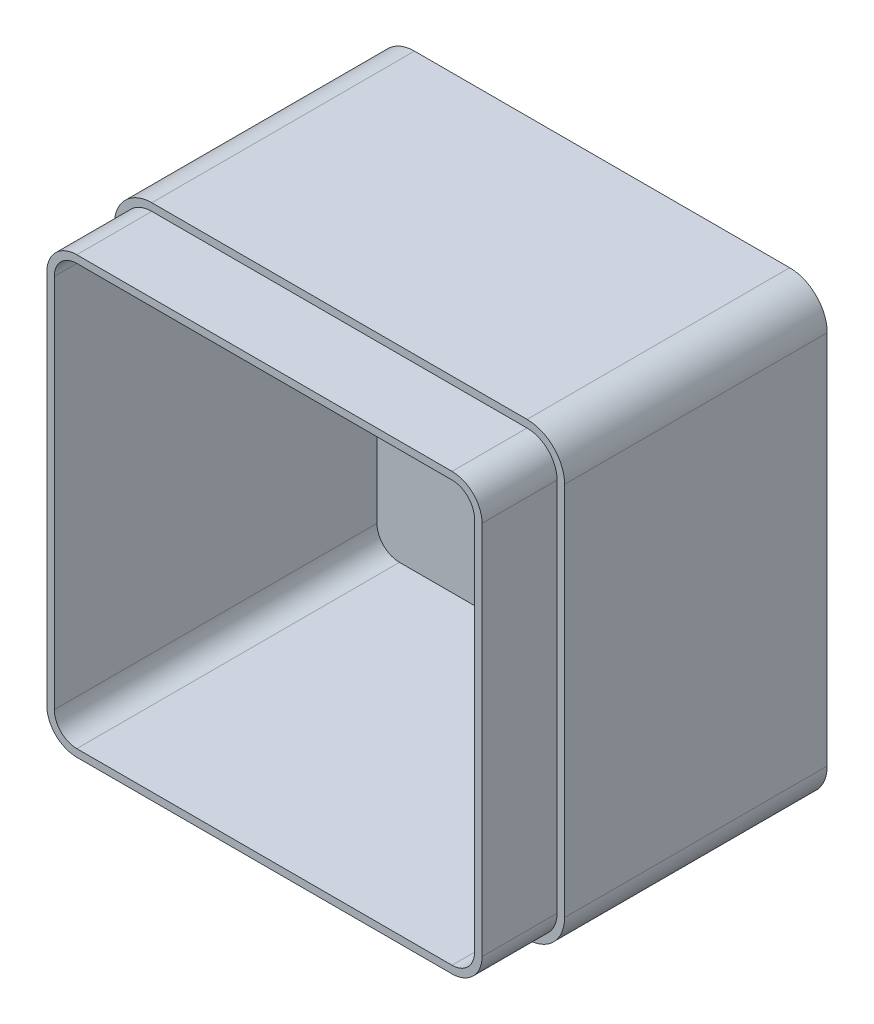
SolidWorks part; units mm, degrees
ref_plane "Front Plane" through (0, 0, 0) normal (0, 0, 1) x (1, 0, 0)
ref_plane "Top Plane" through (0, 0, 0) normal (0, 1, 0) x (1, 0, 0)
ref_plane "Right Plane" through (0, 0, 0) normal (1, 0, 0) x (0, 0, -1)
sketch "Sketch1" plane through (0, 0, 0) normal (0, 0, 1) x (1, 0, 0)
  line L1 (0, 0) -> (120, 0)
  line L2 (0, 0) -> (0, -120)
  line L3 (0, -120) -> (120, -120)
  line L4 (120, 0) -> (120, -120)
  dimension "D1" = 120
  dimension "D2" = 120
extrude "Boss-Extrude1" add sketch "Sketch1" along normal blind 90
fillet "Fillet1" radius 10 4 edges at (0, -120, 45) (120, -120, 45) (120, 0, 45) (0, 0, 45)
shell "Shell1" thickness 4
sketch "Sketch4" plane through (0, 0, 90) normal (0, 0, 1) x (1, 0, 0)
  line L0 (2, -10) -> (2, -110)
  line L1 (10, -118) -> (110, -118)
  line L2 (118, -110) -> (118, -10)
  line L3 (110, -2) -> (10, -2)
  line L4 (0, -10) -> (0, -110)
  line L5 (10, -120) -> (110, -120)
  line L6 (120, -110) -> (120, -10)
  line L7 (110, 0) -> (10, 0)
  line L8 (0, -10) -> (0, -110)
  line L9 (10, -120) -> (110, -120)
  line L10 (120, -110) -> (120, -10)
  line L11 (110, 0) -> (10, 0)
  arc A0 (2, -110) -> (10, -118) centre (10, -110) ccw
  arc A1 (110, -118) -> (118, -110) centre (110, -110) ccw
  arc A2 (118, -10) -> (110, -2) centre (110, -10) ccw
  arc A3 (10, -2) -> (2, -10) centre (10, -10) ccw
  arc A4 (0, -110) -> (10, -120) centre (10, -110) ccw
  arc A5 (110, -120) -> (120, -110) centre (110, -110) ccw
  arc A6 (120, -10) -> (110, 0) centre (110, -10) ccw
  arc A7 (10, 0) -> (0, -10) centre (10, -10) ccw
  arc A8 (0, -110) -> (10, -120) centre (10, -110) ccw
  arc A9 (110, -120) -> (120, -110) centre (110, -110) ccw
  arc A10 (120, -10) -> (110, 0) centre (110, -10) ccw
  arc A11 (10, 0) -> (0, -10) centre (10, -10) ccw
  dimension "D1" = 0
  dimension "D2" = 2
extrude "Cut-Extrude7" cut sketch "Sketch4" against normal blind 20
